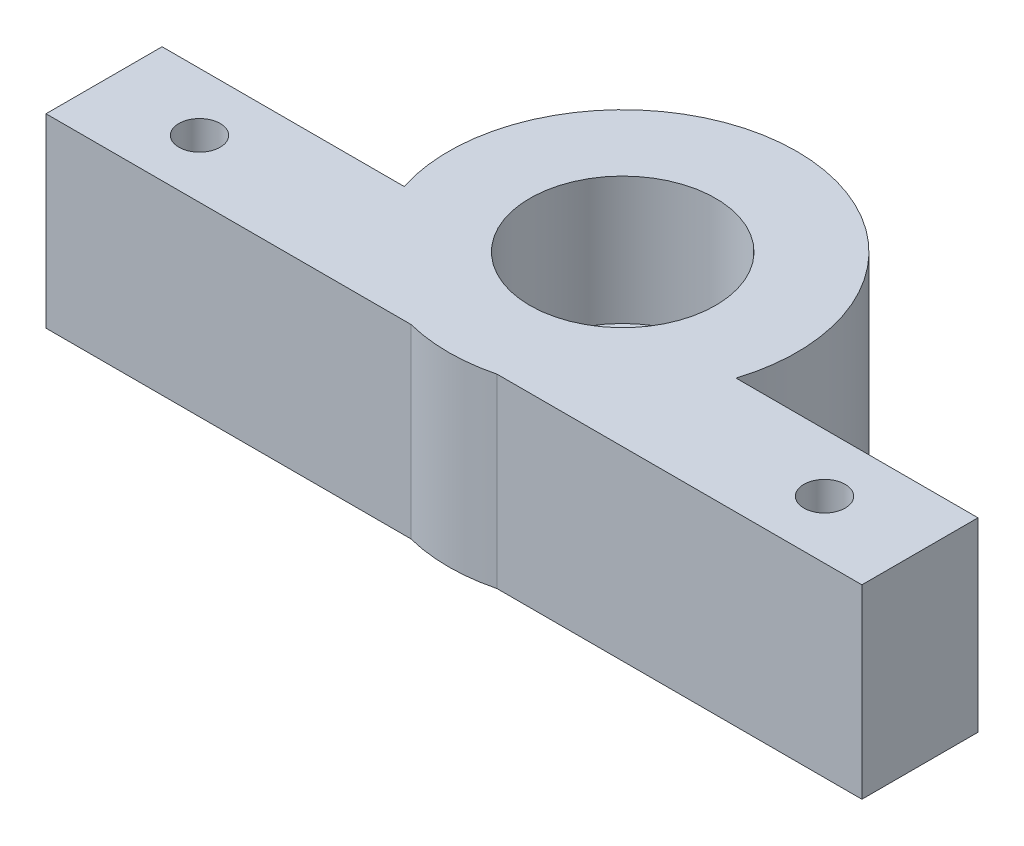
SolidWorks part; units mm, degrees
ref_plane "Front Plane" through (0, 0, 0) normal (0, 0, 1) x (1, 0, 0)
ref_plane "Top Plane" through (0, 0, 0) normal (0, 1, 0) x (1, 0, 0)
ref_plane "Right Plane" through (0, 0, 0) normal (1, 0, 0) x (0, 0, -1)
sketch "Sketch1" plane through (0, 0, 0) normal (0, 1, 0) x (1, 0, 0)
  line L0 (-7.1489, -2.2677) -> (-17.5725, -2.2677)
  line L1 (-17.5725, -2.2677) -> (-17.5725, -7.2677)
  line L3 (-17.5725, -7.2677) -> (-1.8521, -7.2677)
  line L4 (-26.3789, 0) -> (26.3789, 0) construction
  line L5 (-7.2243, -2.2677) -> (-18.1163, -2.2677) construction
  line L6 (7.0711, -7.2677) -> (26.3789, -7.2677) construction
  line L7 (0, 0) -> (0, 16.7972) construction
  line L8 (7.1489, -2.2677) -> (17.5696, -2.2677)
  line L9 (17.5696, -2.2677) -> (17.5696, -7.2677)
  line L10 (17.5696, -7.2677) -> (1.8521, -7.2677)
  arc A0 (-1.8521, -7.2677) -> (1.8521, -7.2677) centre (0, 0) ccw
  arc A1 (7.1489, -2.2677) -> (-7.1489, -2.2677) centre (0, 0) ccw
  circle A3 centre (0, 0) radius 1.875
  circle A5 centre (-13.46, -4.7677) radius 0.889
  circle A6 centre (13.46, -4.7677) radius 0.889
  dimension "D3" = 15
  dimension "D5" = 3.75
  dimension "D6" = 35.1421
  dimension "D2" = 13.46
  dimension "D7" = 1.778
  dimension "D8" = 1.778
  dimension "D10" = 2.5
  dimension "D11" = 13.46
  dimension "D4" = 5
  dimension "D9" = 2.5
extrude "Boss-Extrude1" add sketch "Sketch1" along normal blind 8
sketch "Sketch2" plane through (0, 8, 0) normal (0, 1, 0) x (1, 0, 0)
  circle A0 centre (0, 0) radius 4
  dimension "D1" = 8
extrude "Cut-Extrude1" cut sketch "Sketch2" against normal blind 5.5
